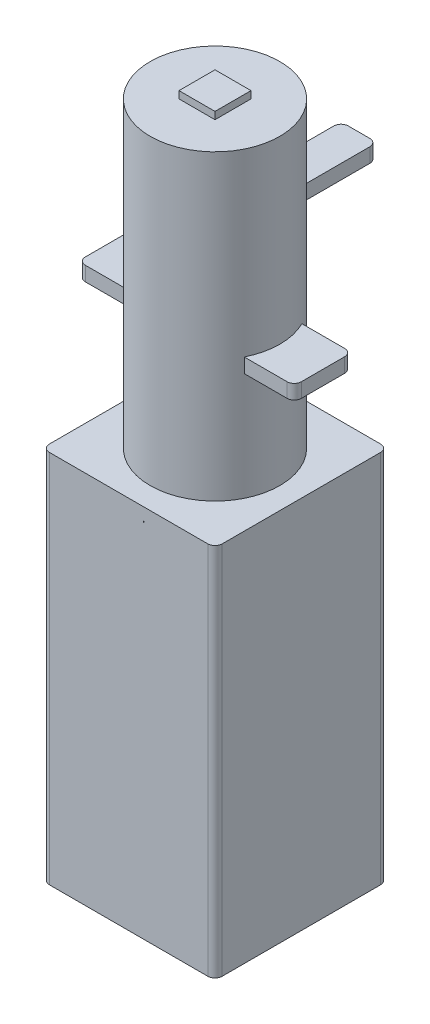
SolidWorks part; units mm, degrees
ref_plane "Front Plane" through (0, 0, 0) normal (0, 0, 1) x (1, 0, 0)
ref_plane "Top Plane" through (0, 0, 0) normal (0, 1, 0) x (1, 0, 0)
ref_plane "Right Plane" through (0, 0, 0) normal (1, 0, 0) x (0, 0, -1)
sketch "Sketch1" plane through (0, 0, 0) normal (0, 1, 0) x (1, 0, 0)
  line L0 (-10.4332, 7.8339) -> (-10.4332, -12.1661)
  line L1 (-12.4332, 9.8339) -> (11.5668, 9.8339)
  line L2 (-12.4332, 9.8339) -> (-12.4332, -14.1661)
  line L3 (-12.4332, -14.1661) -> (11.5668, -14.1661)
  line L4 (11.5668, 9.8339) -> (11.5668, -14.1661)
  line L5 (-10.4332, -12.1661) -> (9.5668, -12.1661)
  line L6 (9.5668, 7.8339) -> (9.5668, -12.1661)
  line L7 (-10.4332, 7.8339) -> (9.5668, 7.8339)
  dimension "D1" = 24
  dimension "24" = 24
  dimension "D2" = 2
extrude "Boss-Extrude1" add sketch "Sketch1" along normal blind 50
fillet "Fillet1" radius 1 4 edges at (-12.4332, 25, 14.1661) (-10.4332, 25, -7.8339) (11.5668, 25, 14.1661) (11.5668, 25, -9.8339)
fillet "Fillet2" radius 1 1 edges at (-12.4332, 25, -9.8339)
sketch "Sketch8" plane through (0, 50, 0) normal (0, 1, 0) x (1, 0, 0)
  line L4 (10.5668, 9.8339) -> (-11.4332, 9.8339)
  line L5 (-12.4332, 8.8339) -> (-12.4332, -13.1661)
  line L6 (-11.4332, -14.1661) -> (10.5668, -14.1661)
  line L7 (11.5668, -13.1661) -> (11.5668, 8.8339)
  line L8 (10.5668, 9.8339) -> (-11.4332, 9.8339)
  line L9 (-12.4332, 8.8339) -> (-12.4332, -13.1661)
  line L10 (-11.4332, -14.1661) -> (10.5668, -14.1661)
  line L11 (11.5668, -13.1661) -> (11.5668, 8.8339)
  arc A4 (-11.4332, 9.8339) -> (-12.4332, 8.8339) centre (-11.4332, 8.8339) ccw
  arc A5 (-12.4332, -13.1661) -> (-11.4332, -14.1661) centre (-11.4332, -13.1661) ccw
  arc A6 (10.5668, -14.1661) -> (11.5668, -13.1661) centre (10.5668, -13.1661) ccw
  arc A7 (11.5668, 8.8339) -> (10.5668, 9.8339) centre (10.5668, 8.8339) ccw
  arc A8 (-11.4332, 9.8339) -> (-12.4332, 8.8339) centre (-11.4332, 8.8339) ccw
  arc A9 (-12.4332, -13.1661) -> (-11.4332, -14.1661) centre (-11.4332, -13.1661) ccw
  arc A10 (10.5668, -14.1661) -> (11.5668, -13.1661) centre (10.5668, -13.1661) ccw
  arc A11 (11.5668, 8.8339) -> (10.5668, 9.8339) centre (10.5668, 8.8339) ccw
  dimension "D1" = 0
extrude "Boss-Extrude7" add sketch "Sketch8" along normal blind 2 contours L8 A8 L9 A9 L10 A10 L11 A11
sketch "Sketch9" plane through (0, 50, 0) normal (0, -1, 0) x (1, 0, 0)
  line L4 (-10.4332, 12.1661) -> (-10.4332, -6.8339)
  line L5 (-9.4332, -7.8339) -> (9.5668, -7.8339)
  line L6 (9.5668, -7.8339) -> (9.5668, 12.1661)
  line L7 (9.5668, 12.1661) -> (-10.4332, 12.1661)
  circle A0 centre (-0.4332, 2.1661) radius 9
  arc A1 (-10.4332, -6.8339) -> (-9.4332, -7.8339) centre (-9.4332, -6.8339) ccw
  arc A2 (-10.4332, -6.8339) -> (-9.4332, -7.8339) centre (-9.4332, -6.8339) ccw
  dimension "D2" = 18
  dimension "D1" = 0
extrude "Boss-Extrude9" add sketch "Sketch9" along normal blind 30 contours A0
sketch "Sketch10" plane through (0, 20, 0) normal (0, -1, 0) x (1, 0, 0)
  circle A0 centre (-0.4332, 2.1661) radius 7
  circle A1 centre (-0.4332, 2.1661) radius 9 construction
  dimension "D1" = 14
extrude "Cut-Extrude1" cut sketch "Sketch10" against normal blind 34
sketch "Sketch11" plane through (0, 52, 0) normal (0, 1, 0) x (1, 0, 0)
  circle A1 centre (-0.4332, -2.1661) radius 9
  circle A2 centre (-0.4332, -2.1661) radius 7 construction
  circle A3 centre (-0.4332, -2.1661) radius 7
  dimension "D2" = 18
extrude "Boss-Extrude10" add sketch "Sketch11" along normal blind 40
ref_plane "Plane2" through (0, 68, 0) normal (0, 1, 0) x (1, 0, 0)
sketch "Sketch14" plane through (0, 68, 0) normal (0, 1, 0) x (1, 0, 0)
  line L0 (7.629, 1.8339) -> (14.5668, 1.8339)
  line L1 (-15.4332, 1.8339) -> (-8.4955, 1.8339)
  line L2 (-15.4332, 1.8339) -> (-15.4332, -6.1661)
  line L3 (-15.4332, -6.1661) -> (-8.4955, -6.1661)
  line L4 (14.5668, 1.8339) -> (14.5668, -6.1661)
  line L5 (7.629, -6.1661) -> (14.5668, -6.1661)
  circle A0 centre (-0.4332, -2.1661) radius 9
  circle A1 centre (-0.4332, -2.1661) radius 9 construction
  dimension "D1" = 18
  dimension "D2" = 15
  dimension "D3" = 15
  dimension "D4" = 4
  dimension "D5" = 4
extrude "Boss-Extrude12" add sketch "Sketch14" along normal mid plane 2 contours A0 L1 L2 L3 | A0 L5 L4 L0
fillet "Fillet3" radius 1 4 edges at (14.5668, 68, 6.1661) (14.5668, 68, -1.8339) (-15.4332, 68, -1.8339) (-15.4332, 68, 6.1661)
sketch "Sketch15" plane through (0, 92, 0) normal (0, 1, 0) x (1, 0, 0)
  circle A1 centre (-0.4332, -2.1661) radius 9
  circle A2 centre (-0.4332, -2.1661) radius 9
  dimension "D1" = 0
extrude "Boss-Extrude13" add sketch "Sketch15" along normal blind 2 contours A2
ref_plane "Plane3" through (0, 79, 0) normal (0, 1, 0) x (1, 0, 0)
sketch "Sketch17" plane through (0, 79, 0) normal (0, 1, 0) x (1, 0, 0)
  line L0 (-12.4332, 8.8339) -> (-12.4332, -13.1661) construction
  line L1 (-2.9332, 17.8339) -> (2.0668, 17.8339)
  line L2 (-2.9332, 17.8339) -> (-2.9332, 6.4797)
  line L4 (2.0668, 17.8339) -> (2.0668, 6.4797)
  circle A0 centre (-0.4332, -2.1661) radius 9
  circle A2 centre (-0.4332, -2.1661) radius 9 construction
  dimension "D1" = 18
  dimension "D2" = 9.5
  dimension "D3" = 5
  dimension "D4" = 20
extrude "Boss-Extrude15" add sketch "Sketch17" along normal mid plane 2 contours A0 L4 L1 L2
fillet "Fillet5" radius 1 2 edges at (2.0668, 79, -17.8339) (-2.9332, 79, -17.8339)
sketch "Sketch18" plane through (0, 94, 0) normal (0, 1, 0) x (1, 0, 0)
  line L0 (11.5668, -13.1661) -> (11.5668, 8.8339) construction
  line L1 (-2.9332, 0.3339) -> (2.0668, 0.3339)
  line L2 (-2.9332, 0.3339) -> (-2.9332, -4.6661)
  line L3 (-2.9332, -4.6661) -> (2.0668, -4.6661)
  line L4 (2.0668, 0.3339) -> (2.0668, -4.6661)
  line L5 (-11.4332, -14.1661) -> (10.5668, -14.1661) construction
  dimension "D1" = 5
  dimension "D2" = 5
  dimension "D3" = 9.5
  dimension "9.5" = 9.5
extrude "Boss-Extrude16" add sketch "Sketch18" along normal mid plane 2
